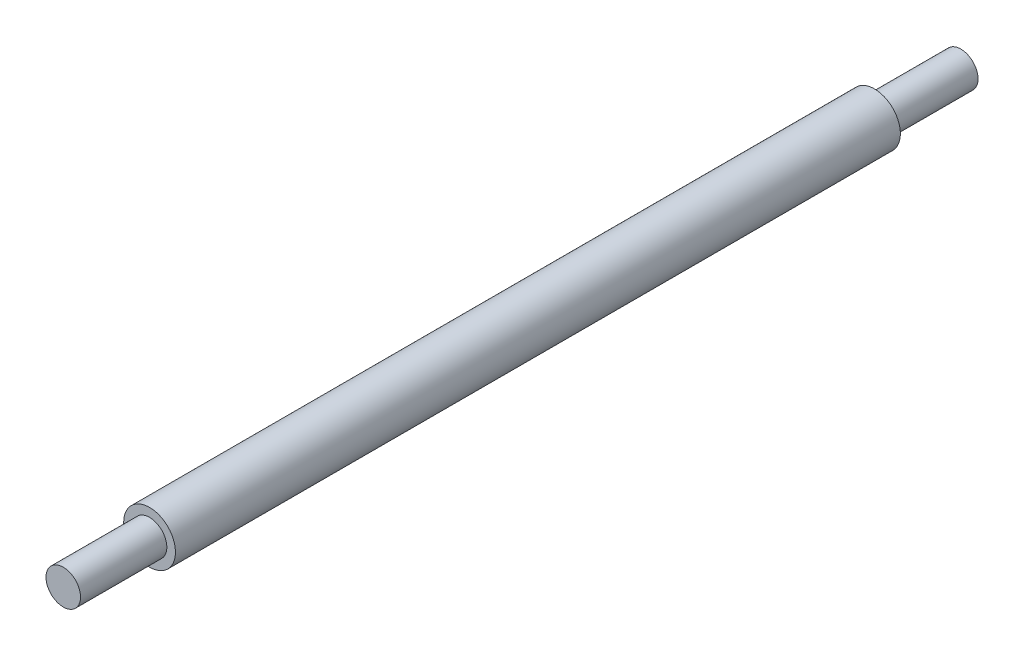
SolidWorks part; units mm, degrees
ref_plane "Front Plane" through (0, 0, 0) normal (0, 0, 1) x (1, 0, 0)
ref_plane "Top Plane" through (0, 0, 0) normal (0, 1, 0) x (1, 0, 0)
ref_plane "Right Plane" through (0, 0, 0) normal (1, 0, 0) x (0, 0, -1)
sketch "Sketch1" plane through (0, 0, 0) normal (1, 0, 0) x (0, 0, -1)
  line L0 (0, 0) -> (0, 2)
  line L1 (0, 2) -> (10, 2)
  line L2 (10, 2) -> (10, 3)
  line L3 (10, 3) -> (94, 3)
  line L4 (94, 3) -> (94, 2)
  line L5 (94, 2) -> (104, 2)
  line L6 (104, 2) -> (104, 0)
  line L7 (104, 0) -> (0, 0)
revolve "Revolve1" add sketch "Sketch1" angle 360 about L7
